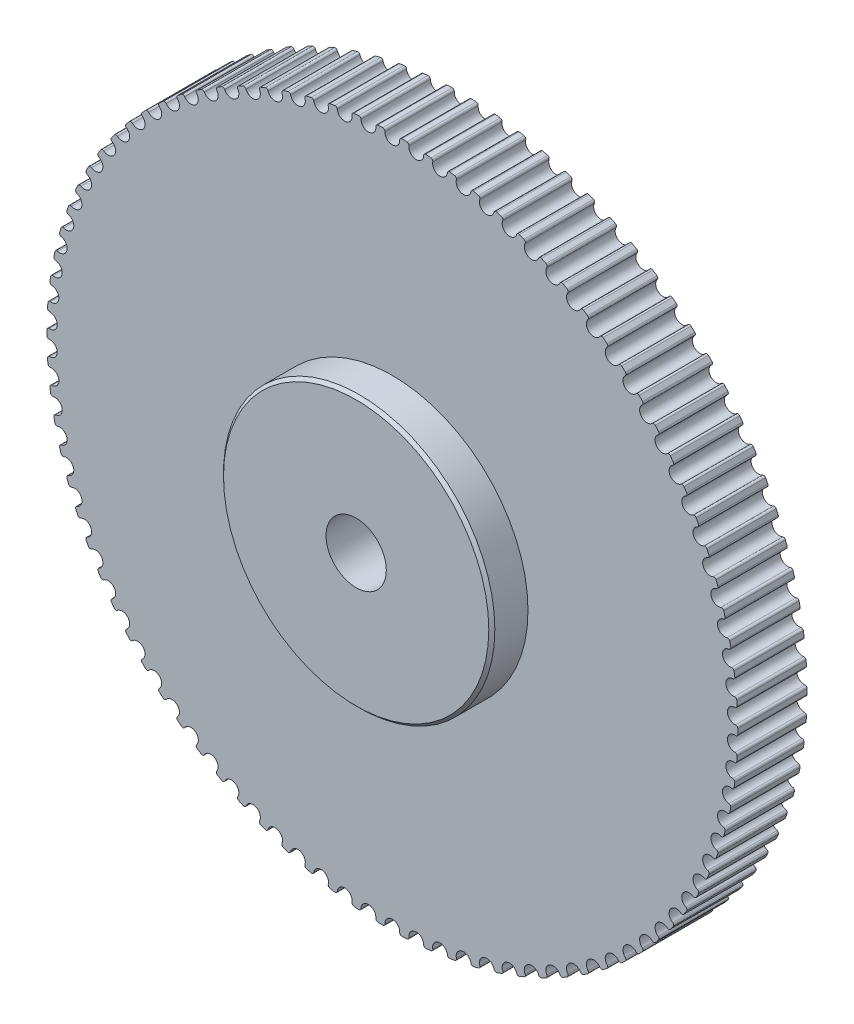
SolidWorks part; units mm, degrees
ref_plane "Ön Düzlem" through (0, 0, 0) normal (0, 0, 1) x (1, 0, 0)
ref_plane "Üst Düzlem" through (0, 0, 0) normal (0, 1, 0) x (1, 0, 0)
ref_plane "Sağ Düzlem" through (0, 0, 0) normal (1, 0, 0) x (0, 0, -1)
sketch "Çizim1" plane through (0, 0, 0) normal (0, 0, 1) x (1, 0, 0)
  arc A2 (0, 111.23) -> (2.457, 113.8116) centre (0, 113.69) ccw
  arc A3 (5.4881, 113.7058) -> (7.759, 110.959) centre (7.9306, 113.4131) ccw
  arc A4 (3.1755, 114.546) -> (2.457, 113.8116) centre (3.1561, 113.8463) ccw
  arc A5 (5.4881, 113.7058) -> (4.8225, 114.4885) centre (4.7931, 113.7891) ccw
  arc A6 (4.8225, 114.4885) -> (3.1755, 114.546) centre (0, 0) ccw
  arc A7 (7.759, 110.959) -> (10.3901, 113.363) centre (7.9306, 113.4131) ccw
  arc A8 (11.1581, 114.0454) -> (10.3901, 113.363) centre (11.09, 113.3488) ccw
  arc A9 (12.7971, 113.8732) -> (11.1581, 114.0454) centre (0, 0) ccw
  arc A10 (13.4064, 113.046) -> (12.7971, 113.8732) centre (12.7189, 113.1776) ccw
  arc A11 (13.4064, 113.046) -> (15.4802, 110.1475) centre (15.8226, 112.5836) ccw
  arc A12 (15.4802, 110.1475) -> (18.2726, 112.3621) centre (15.8226, 112.5836) ccw
  arc A13 (19.0863, 112.9893) -> (18.2726, 112.3621) centre (18.9698, 112.2991) ccw
  arc A14 (20.7093, 112.7031) -> (19.0863, 112.9893) centre (0, 0) ccw
  arc A15 (21.2595, 111.8354) -> (20.7093, 112.7031) centre (20.5828, 112.0146) ccw
  arc A16 (21.2595, 111.8354) -> (23.126, 108.7994) centre (23.6375, 111.2056) ccw
  arc A17 (23.126, 108.7994) -> (26.0661, 110.8138) centre (23.6375, 111.2056) ccw
  arc A18 (26.9216, 111.3827) -> (26.0661, 110.8138) centre (26.7571, 110.7022) ccw
  arc A19 (28.5206, 110.984) -> (26.9216, 111.3827) centre (0, 0) ccw
  arc A20 (29.0089, 110.08) -> (28.5206, 110.984) centre (28.3464, 110.306) ccw
  arc A21 (29.0089, 110.08) -> (30.6591, 106.9211) centre (31.3372, 109.2858) ccw
  arc A22 (30.6591, 106.9211) -> (33.7326, 108.7255) centre (31.3372, 109.2858) ccw
  arc A23 (34.6257, 109.2334) -> (33.7326, 108.7255) centre (34.4142, 108.5661) ccw
  arc A24 (36.193, 108.7241) -> (34.6257, 109.2334) centre (0, 0) ccw
  arc A25 (36.6171, 107.7883) -> (36.193, 108.7241) centre (35.9719, 108.06) ccw
  arc A26 (36.6171, 107.7883) -> (38.0429, 104.522) centre (38.8843, 106.8337) ccw
  arc A27 (38.0429, 104.522) -> (41.2347, 106.1076) centre (38.8843, 106.8337) ccw
  arc A28 (42.1611, 106.5519) -> (41.2347, 106.1076) centre (41.9035, 105.901) ccw
  arc A29 (43.6891, 105.9346) -> (42.1611, 106.5519) centre (0, 0) ccw
  arc A30 (44.0468, 104.9715) -> (43.6891, 105.9346) centre (43.4222, 105.2874) ccw
  arc A31 (44.0468, 104.9715) -> (45.2413, 101.6137) centre (46.2419, 103.861) ccw
  arc A32 (45.2413, 101.6137) -> (48.5359, 102.9728) centre (46.2419, 103.861) ccw
  arc A33 (49.491, 103.3514) -> (48.5359, 102.9728) centre (49.1887, 102.72) ccw
  arc A34 (50.9723, 102.6289) -> (49.491, 103.3514) centre (0, 0) ccw
  arc A35 (51.2619, 101.6432) -> (50.9723, 102.6289) centre (50.6609, 102.002) ccw
  arc A36 (51.2619, 101.6432) -> (52.2193, 98.2103) centre (53.3742, 100.3823) ccw
  arc A37 (52.2193, 98.2103) -> (55.6007, 99.3362) centre (53.3742, 100.3823) ccw
  arc A38 (56.5799, 99.6473) -> (55.6007, 99.3362) centre (56.2343, 99.0386) ccw
  arc A39 (58.0071, 98.8233) -> (56.5799, 99.6473) centre (0, 0) ccw
  arc A40 (58.2273, 97.8198) -> (58.0071, 98.8233) centre (57.6528, 98.2196) ccw
  arc A41 (58.2273, 97.8198) -> (58.9429, 94.3284) centre (60.2465, 96.4146) ccw
  arc A42 (58.9429, 94.3284) -> (62.3946, 95.2157) centre (60.2465, 96.4146) ccw
  arc A43 (63.3931, 95.4577) -> (62.3946, 95.2157) centre (63.0059, 94.8746) ccw
  arc A44 (64.7594, 94.5362) -> (63.3931, 95.4577) centre (0, 0) ccw
  arc A45 (64.9091, 93.5197) -> (64.7594, 94.5362) centre (64.3638, 93.9587) ccw
  arc A46 (64.9091, 93.5197) -> (65.3794, 89.987) centre (66.8253, 91.9771) ccw
  arc A47 (65.3794, 89.987) -> (68.8846, 90.6314) centre (66.8253, 91.9771) ccw
  arc A48 (69.8975, 90.8031) -> (68.8846, 90.6314) centre (69.4705, 90.2484) ccw
  arc A49 (71.1961, 89.7885) -> (69.8975, 90.8031) centre (0, 0) ccw
  arc A50 (71.2746, 88.7641) -> (71.1961, 89.7885) centre (70.7612, 89.24) ccw
  arc A51 (71.2746, 88.7641) -> (71.4973, 85.2071) centre (73.0785, 87.0916) ccw
  arc A52 (71.4973, 85.2071) -> (75.0389, 85.6055) centre (73.0785, 87.0916) ccw
  arc A53 (76.0613, 85.7061) -> (75.0389, 85.6055) centre (75.5967, 85.1826) ccw
  arc A54 (77.286, 84.6034) -> (76.0613, 85.7061) centre (0, 0) ccw
  arc A55 (77.2928, 83.576) -> (77.286, 84.6034) centre (76.8139, 84.0866) ccw
  arc A56 (77.2928, 83.576) -> (77.2669, 80.0122) centre (78.9757, 81.7817) ccw
  arc A57 (77.2669, 80.0122) -> (80.8276, 80.1625) centre (78.9757, 81.7817) ccw
  arc A58 (81.8546, 80.1916) -> (80.8276, 80.1625) centre (81.3546, 79.7017) ccw
  arc A59 (82.9994, 79.0061) -> (81.8546, 80.1916) centre (0, 0) ccw
  arc A60 (82.9345, 77.9808) -> (82.9994, 79.0061) centre (82.4924, 78.5235) ccw
  arc A61 (82.9345, 77.9808) -> (82.66, 74.4274) centre (84.4881, 76.0735) ccw
  arc A62 (82.66, 74.4274) -> (86.2226, 74.329) centre (84.4881, 76.0735) ccw
  arc A63 (87.2491, 74.2863) -> (86.2226, 74.329) centre (86.7161, 73.8326) ccw
  arc A64 (88.3084, 73.0239) -> (87.2491, 74.2863) centre (0, 0) ccw
  arc A65 (88.1721, 72.0056) -> (88.3084, 73.0239) centre (87.769, 72.5778) ccw
  arc A66 (88.1721, 72.0056) -> (87.6504, 68.48) centre (89.5889, 69.9946) ccw
  arc A67 (87.6504, 68.48) -> (91.1975, 68.1333) centre (89.5889, 69.9946) ccw
  arc A68 (92.2185, 68.0192) -> (91.1975, 68.1333) centre (91.6552, 67.6037) ccw
  arc A69 (93.1872, 66.6859) -> (92.2185, 68.0192) centre (0, 0) ccw
  arc A70 (92.9802, 65.6796) -> (93.1872, 66.6859) centre (92.6179, 66.2786) ccw
  arc A71 (92.9802, 65.6796) -> (92.2138, 62.199) centre (94.2533, 63.5746) ccw
  arc A72 (92.2138, 62.199) -> (95.7281, 61.6057) centre (94.2533, 63.5746) ccw
  arc A73 (96.7387, 61.4207) -> (95.7281, 61.6057) centre (96.1477, 61.0455) ccw
  arc A74 (97.612, 60.0231) -> (96.7387, 61.4207) centre (0, 0) ccw
  arc A75 (97.3353, 59.0336) -> (97.612, 60.0231) centre (97.0157, 59.6564) ccw
  arc A76 (97.3353, 59.0336) -> (96.328, 55.615) centre (98.4584, 56.845) ccw
  arc A77 (96.328, 55.615) -> (99.7923, 54.778) centre (98.4584, 56.845) ccw
  arc A78 (100.7875, 54.5229) -> (99.7923, 54.778) centre (100.1718, 54.1898) ccw
  arc A79 (101.5612, 53.0678) -> (100.7875, 54.5229) centre (0, 0) ccw
  arc A80 (101.2162, 52.1001) -> (101.5612, 53.0678) centre (100.9408, 52.7436) ccw
  arc A81 (101.2162, 52.1001) -> (99.9729, 48.76) centre (102.1839, 49.8384) ccw
  arc A82 (99.9729, 48.76) -> (103.3703, 47.6834) centre (102.1839, 49.8384) ccw
  arc A83 (104.3453, 47.3595) -> (103.3703, 47.6834) centre (103.7079, 47.0702) ccw
  arc A84 (105.0156, 45.854) -> (104.3453, 47.3595) centre (0, 0) ccw
  arc A85 (104.6039, 44.9127) -> (105.0156, 45.854) centre (104.3741, 45.5739) ccw
  arc A86 (104.6039, 44.9127) -> (103.1307, 41.6675) centre (105.4115, 42.589) ccw
  arc A87 (103.1307, 41.6675) -> (106.4447, 40.3565) centre (105.4115, 42.589) ccw
  arc A88 (107.3948, 39.9654) -> (106.4447, 40.3565) centre (106.7387, 39.7212) ccw
  arc A89 (107.9584, 38.4168) -> (107.3948, 39.9654) centre (0, 0) ccw
  arc A90 (107.4821, 37.5065) -> (107.9584, 38.4168) centre (107.2989, 38.1821) ccw
  arc A91 (107.4821, 37.5065) -> (105.786, 34.372) centre (108.1256, 35.1321) ccw
  arc A92 (105.786, 34.372) -> (109.0006, 32.833) centre (108.1256, 35.1321) ccw
  arc A93 (109.921, 32.3765) -> (109.0006, 32.833) centre (109.2495, 32.1788) ccw
  arc A94 (110.3753, 30.7924) -> (109.921, 32.3765) centre (0, 0) ccw
  arc A95 (109.8366, 29.9175) -> (110.3753, 30.7924) centre (109.701, 30.6043) ccw
  arc A96 (109.8366, 29.9175) -> (107.926, 26.909) centre (110.3129, 27.5041) ccw
  arc A97 (107.926, 26.909) -> (111.0254, 25.1495) centre (110.3129, 27.5041) ccw
  arc A98 (111.9117, 24.63) -> (111.0254, 25.1495) centre (111.2281, 24.4795) ccw
  arc A99 (112.2544, 23.018) -> (111.9117, 24.63) centre (0, 0) ccw
  arc A100 (111.6559, 22.1828) -> (112.2544, 23.018) centre (111.5686, 22.8774) ccw
  arc A101 (111.6559, 22.1828) -> (109.5402, 19.3149) centre (111.9628, 19.7421) ccw
  arc A102 (109.5402, 19.3149) -> (112.5092, 17.3435) centre (111.9628, 19.7421) ccw
  arc A103 (113.3572, 16.7634) -> (112.5092, 17.3435) centre (112.6647, 16.661) ccw
  arc A104 (113.5866, 15.1315) -> (113.3572, 16.7634) centre (0, 0) ccw
  arc A105 (112.9313, 14.3401) -> (113.5866, 15.1315) centre (112.8927, 15.039) ccw
  arc A106 (112.9313, 14.3401) -> (110.6207, 11.6267) centre (113.0672, 11.8838) ccw
  arc A107 (110.6207, 11.6267) -> (113.445, 9.453) centre (113.0672, 11.8838) ccw
  arc A108 (114.2504, 8.8152) -> (113.445, 9.453) centre (113.5525, 8.7613) ccw
  arc A109 (114.3654, 7.1712) -> (114.2504, 8.8152) centre (0, 0) ccw
  arc A110 (113.6566, 6.4275) -> (114.3654, 7.1712) centre (113.6668, 7.1274) ccw
  arc A111 (113.6566, 6.4275) -> (111.1622, 3.8819) centre (113.6207, 3.9677) ccw
  arc A112 (111.1622, 3.8819) -> (113.8281, 1.5165) centre (113.6207, 3.9677) ccw
  arc A113 (114.587, 0.824) -> (113.8281, 1.5165) centre (113.8871, 0.819) ccw
  arc A114 (114.587, -0.824) -> (114.587, 0.824) centre (0, 0) ccw
  arc A115 (113.8281, -1.5165) -> (114.587, -0.824) centre (113.8871, -0.819) ccw
  arc A116 (113.8281, -1.5165) -> (111.1622, -3.8819) centre (113.6207, -3.9677) ccw
  arc A117 (111.1622, -3.8819) -> (113.6566, -6.4275) centre (113.6207, -3.9677) ccw
  arc A118 (114.3654, -7.1712) -> (113.6566, -6.4275) centre (113.6668, -7.1274) ccw
  arc A119 (114.2504, -8.8152) -> (114.3654, -7.1712) centre (0, 0) ccw
  arc A120 (113.445, -9.453) -> (114.2504, -8.8152) centre (113.5525, -8.7613) ccw
  arc A121 (113.445, -9.453) -> (110.6207, -11.6267) centre (113.0672, -11.8838) ccw
  arc A122 (110.6207, -11.6267) -> (112.9313, -14.3401) centre (113.0672, -11.8838) ccw
  arc A123 (113.5866, -15.1315) -> (112.9313, -14.3401) centre (112.8927, -15.039) ccw
  arc A124 (113.3572, -16.7634) -> (113.5866, -15.1315) centre (0, 0) ccw
  arc A125 (112.5092, -17.3435) -> (113.3572, -16.7634) centre (112.6647, -16.661) ccw
  arc A126 (112.5092, -17.3435) -> (109.5402, -19.3149) centre (111.9628, -19.7421) ccw
  arc A127 (109.5402, -19.3149) -> (111.6559, -22.1828) centre (111.9628, -19.7421) ccw
  arc A128 (112.2544, -23.018) -> (111.6559, -22.1828) centre (111.5686, -22.8774) ccw
  arc A129 (111.9117, -24.63) -> (112.2544, -23.018) centre (0, 0) ccw
  arc A130 (111.0254, -25.1495) -> (111.9117, -24.63) centre (111.2281, -24.4795) ccw
  arc A131 (111.0254, -25.1495) -> (107.926, -26.909) centre (110.3129, -27.5041) ccw
  arc A132 (107.926, -26.909) -> (109.8366, -29.9175) centre (110.3129, -27.5041) ccw
  arc A133 (110.3753, -30.7924) -> (109.8366, -29.9175) centre (109.701, -30.6043) ccw
  arc A134 (109.921, -32.3765) -> (110.3753, -30.7924) centre (0, 0) ccw
  arc A135 (109.0006, -32.833) -> (109.921, -32.3765) centre (109.2495, -32.1788) ccw
  arc A136 (109.0006, -32.833) -> (105.786, -34.372) centre (108.1256, -35.1321) ccw
  arc A137 (105.786, -34.372) -> (107.4821, -37.5065) centre (108.1256, -35.1321) ccw
  arc A138 (107.9584, -38.4168) -> (107.4821, -37.5065) centre (107.2989, -38.1821) ccw
  arc A139 (107.3948, -39.9654) -> (107.9584, -38.4168) centre (0, 0) ccw
  arc A140 (106.4447, -40.3565) -> (107.3948, -39.9654) centre (106.7387, -39.7212) ccw
  arc A141 (106.4447, -40.3565) -> (103.1307, -41.6675) centre (105.4115, -42.589) ccw
  arc A142 (103.1307, -41.6675) -> (104.6039, -44.9127) centre (105.4115, -42.589) ccw
  arc A143 (105.0156, -45.854) -> (104.6039, -44.9127) centre (104.3741, -45.5739) ccw
  arc A144 (104.3453, -47.3595) -> (105.0156, -45.854) centre (0, 0) ccw
  arc A145 (103.3703, -47.6834) -> (104.3453, -47.3595) centre (103.7079, -47.0702) ccw
  arc A146 (103.3703, -47.6834) -> (99.9729, -48.76) centre (102.1839, -49.8384) ccw
  arc A147 (99.9729, -48.76) -> (101.2162, -52.1001) centre (102.1839, -49.8384) ccw
  arc A148 (101.5612, -53.0678) -> (101.2162, -52.1001) centre (100.9408, -52.7436) ccw
  arc A149 (100.7875, -54.5229) -> (101.5612, -53.0678) centre (0, 0) ccw
  arc A150 (99.7923, -54.778) -> (100.7875, -54.5229) centre (100.1718, -54.1898) ccw
  arc A151 (99.7923, -54.778) -> (96.328, -55.615) centre (98.4584, -56.845) ccw
  arc A152 (96.328, -55.615) -> (97.3353, -59.0336) centre (98.4584, -56.845) ccw
  arc A153 (97.612, -60.0231) -> (97.3353, -59.0336) centre (97.0157, -59.6564) ccw
  arc A154 (96.7387, -61.4207) -> (97.612, -60.0231) centre (0, 0) ccw
  arc A155 (95.7281, -61.6057) -> (96.7387, -61.4207) centre (96.1477, -61.0455) ccw
  arc A156 (95.7281, -61.6057) -> (92.2138, -62.199) centre (94.2533, -63.5746) ccw
  arc A157 (92.2138, -62.199) -> (92.9802, -65.6796) centre (94.2533, -63.5746) ccw
  arc A158 (93.1872, -66.6859) -> (92.9802, -65.6796) centre (92.6179, -66.2786) ccw
  arc A159 (92.2185, -68.0192) -> (93.1872, -66.6859) centre (0, 0) ccw
  arc A160 (91.1975, -68.1333) -> (92.2185, -68.0192) centre (91.6552, -67.6037) ccw
  arc A161 (91.1975, -68.1333) -> (87.6504, -68.48) centre (89.5889, -69.9946) ccw
  arc A162 (87.6504, -68.48) -> (88.1721, -72.0056) centre (89.5889, -69.9946) ccw
  arc A163 (88.3084, -73.0239) -> (88.1721, -72.0056) centre (87.769, -72.5778) ccw
  arc A164 (87.2491, -74.2863) -> (88.3084, -73.0239) centre (0, 0) ccw
  arc A165 (86.2226, -74.329) -> (87.2491, -74.2863) centre (86.7161, -73.8326) ccw
  arc A166 (86.2226, -74.329) -> (82.66, -74.4274) centre (84.4881, -76.0735) ccw
  arc A167 (82.66, -74.4274) -> (82.9345, -77.9808) centre (84.4881, -76.0735) ccw
  arc A168 (82.9994, -79.0061) -> (82.9345, -77.9808) centre (82.4924, -78.5235) ccw
  arc A169 (81.8546, -80.1916) -> (82.9994, -79.0061) centre (0, 0) ccw
  arc A170 (80.8276, -80.1625) -> (81.8546, -80.1916) centre (81.3546, -79.7017) ccw
  arc A171 (80.8276, -80.1625) -> (77.2669, -80.0122) centre (78.9757, -81.7817) ccw
  arc A172 (77.2669, -80.0122) -> (77.2928, -83.576) centre (78.9757, -81.7817) ccw
  arc A173 (77.286, -84.6034) -> (77.2928, -83.576) centre (76.8139, -84.0866) ccw
  arc A174 (76.0613, -85.7061) -> (77.286, -84.6034) centre (0, 0) ccw
  arc A175 (75.0389, -85.6055) -> (76.0613, -85.7061) centre (75.5967, -85.1826) ccw
  arc A176 (75.0389, -85.6055) -> (71.4973, -85.2071) centre (73.0785, -87.0916) ccw
  arc A177 (71.4973, -85.2071) -> (71.2746, -88.7641) centre (73.0785, -87.0916) ccw
  arc A178 (71.1961, -89.7885) -> (71.2746, -88.7641) centre (70.7612, -89.24) ccw
  arc A179 (69.8975, -90.8031) -> (71.1961, -89.7885) centre (0, 0) ccw
  arc A180 (68.8846, -90.6314) -> (69.8975, -90.8031) centre (69.4705, -90.2484) ccw
  arc A181 (68.8846, -90.6314) -> (65.3794, -89.987) centre (66.8253, -91.9771) ccw
  arc A182 (65.3794, -89.987) -> (64.9091, -93.5197) centre (66.8253, -91.9771) ccw
  arc A183 (64.7594, -94.5362) -> (64.9091, -93.5197) centre (64.3638, -93.9587) ccw
  arc A184 (63.3931, -95.4577) -> (64.7594, -94.5362) centre (0, 0) ccw
  arc A185 (62.3946, -95.2157) -> (63.3931, -95.4577) centre (63.0059, -94.8746) ccw
  arc A186 (62.3946, -95.2157) -> (58.9429, -94.3284) centre (60.2465, -96.4146) ccw
  arc A187 (58.9429, -94.3284) -> (58.2273, -97.8198) centre (60.2465, -96.4146) ccw
  arc A188 (58.0071, -98.8233) -> (58.2273, -97.8198) centre (57.6528, -98.2196) ccw
  arc A189 (56.5799, -99.6473) -> (58.0071, -98.8233) centre (0, 0) ccw
  arc A190 (55.6007, -99.3362) -> (56.5799, -99.6473) centre (56.2343, -99.0386) ccw
  arc A191 (55.6007, -99.3362) -> (52.2193, -98.2103) centre (53.3742, -100.3823) ccw
  arc A192 (52.2193, -98.2103) -> (51.2619, -101.6432) centre (53.3742, -100.3823) ccw
  arc A193 (50.9723, -102.6289) -> (51.2619, -101.6432) centre (50.6609, -102.002) ccw
  arc A194 (49.491, -103.3514) -> (50.9723, -102.6289) centre (0, 0) ccw
  arc A195 (48.5359, -102.9728) -> (49.491, -103.3514) centre (49.1887, -102.72) ccw
  arc A196 (48.5359, -102.9728) -> (45.2413, -101.6137) centre (46.2419, -103.861) ccw
  arc A197 (45.2413, -101.6137) -> (44.0468, -104.9715) centre (46.2419, -103.861) ccw
  arc A198 (43.6891, -105.9346) -> (44.0468, -104.9715) centre (43.4222, -105.2874) ccw
  arc A199 (42.1611, -106.5519) -> (43.6891, -105.9346) centre (0, 0) ccw
  arc A200 (41.2347, -106.1076) -> (42.1611, -106.5519) centre (41.9035, -105.901) ccw
  arc A201 (41.2347, -106.1076) -> (38.0429, -104.522) centre (38.8843, -106.8337) ccw
  arc A202 (38.0429, -104.522) -> (36.6171, -107.7883) centre (38.8843, -106.8337) ccw
  arc A203 (36.193, -108.7241) -> (36.6171, -107.7883) centre (35.9719, -108.06) ccw
  arc A204 (34.6257, -109.2334) -> (36.193, -108.7241) centre (0, 0) ccw
  arc A205 (33.7326, -108.7255) -> (34.6257, -109.2334) centre (34.4142, -108.5661) ccw
  arc A206 (33.7326, -108.7255) -> (30.6591, -106.9211) centre (31.3372, -109.2858) ccw
  arc A207 (30.6591, -106.9211) -> (29.0089, -110.08) centre (31.3372, -109.2858) ccw
  arc A208 (28.5206, -110.984) -> (29.0089, -110.08) centre (28.3464, -110.306) ccw
  arc A209 (26.9216, -111.3827) -> (28.5206, -110.984) centre (0, 0) ccw
  arc A210 (26.0661, -110.8138) -> (26.9216, -111.3827) centre (26.7571, -110.7022) ccw
  arc A211 (26.0661, -110.8138) -> (23.126, -108.7994) centre (23.6375, -111.2056) ccw
  arc A212 (23.126, -108.7994) -> (21.2595, -111.8354) centre (23.6375, -111.2056) ccw
  arc A213 (20.7093, -112.7031) -> (21.2595, -111.8354) centre (20.5828, -112.0146) ccw
  arc A214 (19.0863, -112.9893) -> (20.7093, -112.7031) centre (0, 0) ccw
  arc A215 (18.2726, -112.3621) -> (19.0863, -112.9893) centre (18.9698, -112.2991) ccw
  arc A216 (18.2726, -112.3621) -> (15.4802, -110.1475) centre (15.8226, -112.5836) ccw
  arc A217 (15.4802, -110.1475) -> (13.4064, -113.046) centre (15.8226, -112.5836) ccw
  arc A218 (12.7971, -113.8732) -> (13.4064, -113.046) centre (12.7189, -113.1776) ccw
  arc A219 (11.1581, -114.0454) -> (12.7971, -113.8732) centre (0, 0) ccw
  arc A220 (10.3901, -113.363) -> (11.1581, -114.0454) centre (11.09, -113.3488) ccw
  arc A221 (10.3901, -113.363) -> (7.759, -110.959) centre (7.9306, -113.4131) ccw
  arc A222 (7.759, -110.959) -> (5.4881, -113.7058) centre (7.9306, -113.4131) ccw
  arc A223 (4.8225, -114.4885) -> (5.4881, -113.7058) centre (4.7931, -113.7891) ccw
  arc A224 (3.1755, -114.546) -> (4.8225, -114.4885) centre (0, 0) ccw
  arc A225 (2.457, -113.8116) -> (3.1755, -114.546) centre (3.1561, -113.8463) ccw
  arc A226 (2.457, -113.8116) -> (0, -111.23) centre (0, -113.69) ccw
  arc A227 (0, -111.23) -> (-2.457, -113.8116) centre (0, -113.69) ccw
  arc A228 (-3.1755, -114.546) -> (-2.457, -113.8116) centre (-3.1561, -113.8463) ccw
  arc A229 (-4.8225, -114.4885) -> (-3.1755, -114.546) centre (0, 0) ccw
  arc A230 (-5.4881, -113.7058) -> (-4.8225, -114.4885) centre (-4.7931, -113.7891) ccw
  arc A231 (-5.4881, -113.7058) -> (-7.759, -110.959) centre (-7.9306, -113.4131) ccw
  arc A232 (-7.759, -110.959) -> (-10.3901, -113.363) centre (-7.9306, -113.4131) ccw
  arc A233 (-11.1581, -114.0454) -> (-10.3901, -113.363) centre (-11.09, -113.3488) ccw
  arc A234 (-12.7971, -113.8732) -> (-11.1581, -114.0454) centre (0, 0) ccw
  arc A235 (-13.4064, -113.046) -> (-12.7971, -113.8732) centre (-12.7189, -113.1776) ccw
  arc A236 (-13.4064, -113.046) -> (-15.4802, -110.1475) centre (-15.8226, -112.5836) ccw
  arc A237 (-15.4802, -110.1475) -> (-18.2726, -112.3621) centre (-15.8226, -112.5836) ccw
  arc A238 (-19.0863, -112.9893) -> (-18.2726, -112.3621) centre (-18.9698, -112.2991) ccw
  arc A239 (-20.7093, -112.7031) -> (-19.0863, -112.9893) centre (0, 0) ccw
  arc A240 (-21.2595, -111.8354) -> (-20.7093, -112.7031) centre (-20.5828, -112.0146) ccw
  arc A241 (-21.2595, -111.8354) -> (-23.126, -108.7994) centre (-23.6375, -111.2056) ccw
  arc A242 (-23.126, -108.7994) -> (-26.0661, -110.8138) centre (-23.6375, -111.2056) ccw
  arc A243 (-26.9216, -111.3827) -> (-26.0661, -110.8138) centre (-26.7571, -110.7022) ccw
  arc A244 (-28.5206, -110.984) -> (-26.9216, -111.3827) centre (0, 0) ccw
  arc A245 (-29.0089, -110.08) -> (-28.5206, -110.984) centre (-28.3464, -110.306) ccw
  arc A246 (-29.0089, -110.08) -> (-30.6591, -106.9211) centre (-31.3372, -109.2858) ccw
  arc A247 (-30.6591, -106.9211) -> (-33.7326, -108.7255) centre (-31.3372, -109.2858) ccw
  arc A248 (-34.6257, -109.2334) -> (-33.7326, -108.7255) centre (-34.4142, -108.5661) ccw
  arc A249 (-36.193, -108.7241) -> (-34.6257, -109.2334) centre (0, 0) ccw
  arc A250 (-36.6171, -107.7883) -> (-36.193, -108.7241) centre (-35.9719, -108.06) ccw
  arc A251 (-36.6171, -107.7883) -> (-38.0429, -104.522) centre (-38.8843, -106.8337) ccw
  arc A252 (-38.0429, -104.522) -> (-41.2347, -106.1076) centre (-38.8843, -106.8337) ccw
  arc A253 (-42.1611, -106.5519) -> (-41.2347, -106.1076) centre (-41.9035, -105.901) ccw
  arc A254 (-43.6891, -105.9346) -> (-42.1611, -106.5519) centre (0, 0) ccw
  arc A255 (-44.0468, -104.9715) -> (-43.6891, -105.9346) centre (-43.4222, -105.2874) ccw
  arc A256 (-44.0468, -104.9715) -> (-45.2413, -101.6137) centre (-46.2419, -103.861) ccw
  arc A257 (-45.2413, -101.6137) -> (-48.5359, -102.9728) centre (-46.2419, -103.861) ccw
  arc A258 (-49.491, -103.3514) -> (-48.5359, -102.9728) centre (-49.1887, -102.72) ccw
  arc A259 (-50.9723, -102.6289) -> (-49.491, -103.3514) centre (0, 0) ccw
  arc A260 (-51.2619, -101.6432) -> (-50.9723, -102.6289) centre (-50.6609, -102.002) ccw
  arc A261 (-51.2619, -101.6432) -> (-52.2193, -98.2103) centre (-53.3742, -100.3823) ccw
  arc A262 (-52.2193, -98.2103) -> (-55.6007, -99.3362) centre (-53.3742, -100.3823) ccw
  arc A263 (-56.5799, -99.6473) -> (-55.6007, -99.3362) centre (-56.2343, -99.0386) ccw
  arc A264 (-58.0071, -98.8233) -> (-56.5799, -99.6473) centre (0, 0) ccw
  arc A265 (-58.2273, -97.8198) -> (-58.0071, -98.8233) centre (-57.6528, -98.2196) ccw
  arc A266 (-58.2273, -97.8198) -> (-58.9429, -94.3284) centre (-60.2465, -96.4146) ccw
  arc A267 (-58.9429, -94.3284) -> (-62.3946, -95.2157) centre (-60.2465, -96.4146) ccw
  arc A268 (-63.3931, -95.4577) -> (-62.3946, -95.2157) centre (-63.0059, -94.8746) ccw
  arc A269 (-64.7594, -94.5362) -> (-63.3931, -95.4577) centre (0, 0) ccw
  arc A270 (-64.9091, -93.5197) -> (-64.7594, -94.5362) centre (-64.3638, -93.9587) ccw
  arc A271 (-64.9091, -93.5197) -> (-65.3794, -89.987) centre (-66.8253, -91.9771) ccw
  arc A272 (-65.3794, -89.987) -> (-68.8846, -90.6314) centre (-66.8253, -91.9771) ccw
  arc A273 (-69.8975, -90.8031) -> (-68.8846, -90.6314) centre (-69.4705, -90.2484) ccw
  arc A274 (-71.1961, -89.7885) -> (-69.8975, -90.8031) centre (0, 0) ccw
  arc A275 (-71.2746, -88.7641) -> (-71.1961, -89.7885) centre (-70.7612, -89.24) ccw
  arc A276 (-71.2746, -88.7641) -> (-71.4973, -85.2071) centre (-73.0785, -87.0916) ccw
  arc A277 (-71.4973, -85.2071) -> (-75.0389, -85.6055) centre (-73.0785, -87.0916) ccw
  arc A278 (-76.0613, -85.7061) -> (-75.0389, -85.6055) centre (-75.5967, -85.1826) ccw
  arc A279 (-77.286, -84.6034) -> (-76.0613, -85.7061) centre (0, 0) ccw
  arc A280 (-77.2928, -83.576) -> (-77.286, -84.6034) centre (-76.8139, -84.0866) ccw
  arc A281 (-77.2928, -83.576) -> (-77.2669, -80.0122) centre (-78.9757, -81.7817) ccw
  arc A282 (-77.2669, -80.0122) -> (-80.8276, -80.1625) centre (-78.9757, -81.7817) ccw
  arc A283 (-81.8546, -80.1916) -> (-80.8276, -80.1625) centre (-81.3546, -79.7017) ccw
  arc A284 (-82.9994, -79.0061) -> (-81.8546, -80.1916) centre (0, 0) ccw
  arc A285 (-82.9345, -77.9808) -> (-82.9994, -79.0061) centre (-82.4924, -78.5235) ccw
  arc A286 (-82.9345, -77.9808) -> (-82.66, -74.4274) centre (-84.4881, -76.0735) ccw
  arc A287 (-82.66, -74.4274) -> (-86.2226, -74.329) centre (-84.4881, -76.0735) ccw
  arc A288 (-87.2491, -74.2863) -> (-86.2226, -74.329) centre (-86.7161, -73.8326) ccw
  arc A289 (-88.3084, -73.0239) -> (-87.2491, -74.2863) centre (0, 0) ccw
  arc A290 (-88.1721, -72.0056) -> (-88.3084, -73.0239) centre (-87.769, -72.5778) ccw
  arc A291 (-88.1721, -72.0056) -> (-87.6504, -68.48) centre (-89.5889, -69.9946) ccw
  arc A292 (-87.6504, -68.48) -> (-91.1975, -68.1333) centre (-89.5889, -69.9946) ccw
  arc A293 (-92.2185, -68.0192) -> (-91.1975, -68.1333) centre (-91.6552, -67.6037) ccw
  arc A294 (-93.1872, -66.6859) -> (-92.2185, -68.0192) centre (0, 0) ccw
  arc A295 (-92.9802, -65.6796) -> (-93.1872, -66.6859) centre (-92.6179, -66.2786) ccw
  arc A296 (-92.9802, -65.6796) -> (-92.2138, -62.199) centre (-94.2533, -63.5746) ccw
  arc A297 (-92.2138, -62.199) -> (-95.7281, -61.6057) centre (-94.2533, -63.5746) ccw
  arc A298 (-96.7387, -61.4207) -> (-95.7281, -61.6057) centre (-96.1477, -61.0455) ccw
  arc A299 (-97.612, -60.0231) -> (-96.7387, -61.4207) centre (0, 0) ccw
  arc A300 (-97.3353, -59.0336) -> (-97.612, -60.0231) centre (-97.0157, -59.6564) ccw
  arc A301 (-97.3353, -59.0336) -> (-96.328, -55.615) centre (-98.4584, -56.845) ccw
  arc A302 (-96.328, -55.615) -> (-99.7923, -54.778) centre (-98.4584, -56.845) ccw
  arc A303 (-100.7875, -54.5229) -> (-99.7923, -54.778) centre (-100.1718, -54.1898) ccw
  arc A304 (-101.5612, -53.0678) -> (-100.7875, -54.5229) centre (0, 0) ccw
  arc A305 (-101.2162, -52.1001) -> (-101.5612, -53.0678) centre (-100.9408, -52.7436) ccw
  arc A306 (-101.2162, -52.1001) -> (-99.9729, -48.76) centre (-102.1839, -49.8384) ccw
  arc A307 (-99.9729, -48.76) -> (-103.3703, -47.6834) centre (-102.1839, -49.8384) ccw
  arc A308 (-104.3453, -47.3595) -> (-103.3703, -47.6834) centre (-103.7079, -47.0702) ccw
  arc A309 (-105.0156, -45.854) -> (-104.3453, -47.3595) centre (0, 0) ccw
  arc A310 (-104.6039, -44.9127) -> (-105.0156, -45.854) centre (-104.3741, -45.5739) ccw
  arc A311 (-104.6039, -44.9127) -> (-103.1307, -41.6675) centre (-105.4115, -42.589) ccw
  arc A312 (-103.1307, -41.6675) -> (-106.4447, -40.3565) centre (-105.4115, -42.589) ccw
  arc A313 (-107.3948, -39.9654) -> (-106.4447, -40.3565) centre (-106.7387, -39.7212) ccw
  arc A314 (-107.9584, -38.4168) -> (-107.3948, -39.9654) centre (0, 0) ccw
  arc A315 (-107.4821, -37.5065) -> (-107.9584, -38.4168) centre (-107.2989, -38.1821) ccw
  arc A316 (-107.4821, -37.5065) -> (-105.786, -34.372) centre (-108.1256, -35.1321) ccw
  arc A317 (-105.786, -34.372) -> (-109.0006, -32.833) centre (-108.1256, -35.1321) ccw
  arc A318 (-109.921, -32.3765) -> (-109.0006, -32.833) centre (-109.2495, -32.1788) ccw
  arc A319 (-110.3753, -30.7924) -> (-109.921, -32.3765) centre (0, 0) ccw
  arc A320 (-109.8366, -29.9175) -> (-110.3753, -30.7924) centre (-109.701, -30.6043) ccw
  arc A321 (-109.8366, -29.9175) -> (-107.926, -26.909) centre (-110.3129, -27.5041) ccw
  arc A322 (-107.926, -26.909) -> (-111.0254, -25.1495) centre (-110.3129, -27.5041) ccw
  arc A323 (-111.9117, -24.63) -> (-111.0254, -25.1495) centre (-111.2281, -24.4795) ccw
  arc A324 (-112.2544, -23.018) -> (-111.9117, -24.63) centre (0, 0) ccw
  arc A325 (-111.6559, -22.1828) -> (-112.2544, -23.018) centre (-111.5686, -22.8774) ccw
  arc A326 (-111.6559, -22.1828) -> (-109.5402, -19.3149) centre (-111.9628, -19.7421) ccw
  arc A327 (-109.5402, -19.3149) -> (-112.5092, -17.3435) centre (-111.9628, -19.7421) ccw
  arc A328 (-113.3572, -16.7634) -> (-112.5092, -17.3435) centre (-112.6647, -16.661) ccw
  arc A329 (-113.5866, -15.1315) -> (-113.3572, -16.7634) centre (0, 0) ccw
  arc A330 (-112.9313, -14.3401) -> (-113.5866, -15.1315) centre (-112.8927, -15.039) ccw
  arc A331 (-112.9313, -14.3401) -> (-110.6207, -11.6267) centre (-113.0672, -11.8838) ccw
  arc A332 (-110.6207, -11.6267) -> (-113.445, -9.453) centre (-113.0672, -11.8838) ccw
  arc A333 (-114.2504, -8.8152) -> (-113.445, -9.453) centre (-113.5525, -8.7613) ccw
  arc A334 (-114.3654, -7.1712) -> (-114.2504, -8.8152) centre (0, 0) ccw
  arc A335 (-113.6566, -6.4275) -> (-114.3654, -7.1712) centre (-113.6668, -7.1274) ccw
  arc A336 (-113.6566, -6.4275) -> (-111.1622, -3.8819) centre (-113.6207, -3.9677) ccw
  arc A337 (-111.1622, -3.8819) -> (-113.8281, -1.5165) centre (-113.6207, -3.9677) ccw
  arc A338 (-114.587, -0.824) -> (-113.8281, -1.5165) centre (-113.8871, -0.819) ccw
  arc A339 (-114.587, 0.824) -> (-114.587, -0.824) centre (0, 0) ccw
  arc A340 (-113.8281, 1.5165) -> (-114.587, 0.824) centre (-113.8871, 0.819) ccw
  arc A341 (-113.8281, 1.5165) -> (-111.1622, 3.8819) centre (-113.6207, 3.9677) ccw
  arc A342 (-111.1622, 3.8819) -> (-113.6566, 6.4275) centre (-113.6207, 3.9677) ccw
  arc A343 (-114.3654, 7.1712) -> (-113.6566, 6.4275) centre (-113.6668, 7.1274) ccw
  arc A344 (-114.2504, 8.8152) -> (-114.3654, 7.1712) centre (0, 0) ccw
  arc A345 (-113.445, 9.453) -> (-114.2504, 8.8152) centre (-113.5525, 8.7613) ccw
  arc A346 (-113.445, 9.453) -> (-110.6207, 11.6267) centre (-113.0672, 11.8838) ccw
  arc A347 (-110.6207, 11.6267) -> (-112.9313, 14.3401) centre (-113.0672, 11.8838) ccw
  arc A348 (-113.5866, 15.1315) -> (-112.9313, 14.3401) centre (-112.8927, 15.039) ccw
  arc A349 (-113.3572, 16.7634) -> (-113.5866, 15.1315) centre (0, 0) ccw
  arc A350 (-112.5092, 17.3435) -> (-113.3572, 16.7634) centre (-112.6647, 16.661) ccw
  arc A351 (-112.5092, 17.3435) -> (-109.5402, 19.3149) centre (-111.9628, 19.7421) ccw
  arc A352 (-109.5402, 19.3149) -> (-111.6559, 22.1828) centre (-111.9628, 19.7421) ccw
  arc A353 (-112.2544, 23.018) -> (-111.6559, 22.1828) centre (-111.5686, 22.8774) ccw
  arc A354 (-111.9117, 24.63) -> (-112.2544, 23.018) centre (0, 0) ccw
  arc A355 (-111.0254, 25.1495) -> (-111.9117, 24.63) centre (-111.2281, 24.4795) ccw
  arc A356 (-111.0254, 25.1495) -> (-107.926, 26.909) centre (-110.3129, 27.5041) ccw
  arc A357 (-107.926, 26.909) -> (-109.8366, 29.9175) centre (-110.3129, 27.5041) ccw
  arc A358 (-110.3753, 30.7924) -> (-109.8366, 29.9175) centre (-109.701, 30.6043) ccw
  arc A359 (-109.921, 32.3765) -> (-110.3753, 30.7924) centre (0, 0) ccw
  arc A360 (-109.0006, 32.833) -> (-109.921, 32.3765) centre (-109.2495, 32.1788) ccw
  arc A361 (-109.0006, 32.833) -> (-105.786, 34.372) centre (-108.1256, 35.1321) ccw
  arc A362 (-105.786, 34.372) -> (-107.4821, 37.5065) centre (-108.1256, 35.1321) ccw
  arc A363 (-107.9584, 38.4168) -> (-107.4821, 37.5065) centre (-107.2989, 38.1821) ccw
  arc A364 (-107.3948, 39.9654) -> (-107.9584, 38.4168) centre (0, 0) ccw
  arc A365 (-106.4447, 40.3565) -> (-107.3948, 39.9654) centre (-106.7387, 39.7212) ccw
  arc A366 (-106.4447, 40.3565) -> (-103.1307, 41.6675) centre (-105.4115, 42.589) ccw
  arc A367 (-103.1307, 41.6675) -> (-104.6039, 44.9127) centre (-105.4115, 42.589) ccw
  arc A368 (-105.0156, 45.854) -> (-104.6039, 44.9127) centre (-104.3741, 45.5739) ccw
  arc A369 (-104.3453, 47.3595) -> (-105.0156, 45.854) centre (0, 0) ccw
  arc A370 (-103.3703, 47.6834) -> (-104.3453, 47.3595) centre (-103.7079, 47.0702) ccw
  arc A371 (-103.3703, 47.6834) -> (-99.9729, 48.76) centre (-102.1839, 49.8384) ccw
  arc A372 (-99.9729, 48.76) -> (-101.2162, 52.1001) centre (-102.1839, 49.8384) ccw
  arc A373 (-101.5612, 53.0678) -> (-101.2162, 52.1001) centre (-100.9408, 52.7436) ccw
  arc A374 (-100.7875, 54.5229) -> (-101.5612, 53.0678) centre (0, 0) ccw
  arc A375 (-99.7923, 54.778) -> (-100.7875, 54.5229) centre (-100.1718, 54.1898) ccw
  arc A376 (-99.7923, 54.778) -> (-96.328, 55.615) centre (-98.4584, 56.845) ccw
  arc A377 (-96.328, 55.615) -> (-97.3353, 59.0336) centre (-98.4584, 56.845) ccw
  arc A378 (-97.612, 60.0231) -> (-97.3353, 59.0336) centre (-97.0157, 59.6564) ccw
  arc A379 (-96.7387, 61.4207) -> (-97.612, 60.0231) centre (0, 0) ccw
  arc A380 (-95.7281, 61.6057) -> (-96.7387, 61.4207) centre (-96.1477, 61.0455) ccw
  arc A381 (-95.7281, 61.6057) -> (-92.2138, 62.199) centre (-94.2533, 63.5746) ccw
  arc A382 (-92.2138, 62.199) -> (-92.9802, 65.6796) centre (-94.2533, 63.5746) ccw
  arc A383 (-93.1872, 66.6859) -> (-92.9802, 65.6796) centre (-92.6179, 66.2786) ccw
  arc A384 (-92.2185, 68.0192) -> (-93.1872, 66.6859) centre (0, 0) ccw
  arc A385 (-91.1975, 68.1333) -> (-92.2185, 68.0192) centre (-91.6552, 67.6037) ccw
  arc A386 (-91.1975, 68.1333) -> (-87.6504, 68.48) centre (-89.5889, 69.9946) ccw
  arc A387 (-87.6504, 68.48) -> (-88.1721, 72.0056) centre (-89.5889, 69.9946) ccw
  arc A388 (-88.3084, 73.0239) -> (-88.1721, 72.0056) centre (-87.769, 72.5778) ccw
  arc A389 (-87.2491, 74.2863) -> (-88.3084, 73.0239) centre (0, 0) ccw
  arc A390 (-86.2226, 74.329) -> (-87.2491, 74.2863) centre (-86.7161, 73.8326) ccw
  arc A391 (-86.2226, 74.329) -> (-82.66, 74.4274) centre (-84.4881, 76.0735) ccw
  arc A392 (-82.66, 74.4274) -> (-82.9345, 77.9808) centre (-84.4881, 76.0735) ccw
  arc A393 (-82.9994, 79.0061) -> (-82.9345, 77.9808) centre (-82.4924, 78.5235) ccw
  arc A394 (-81.8546, 80.1916) -> (-82.9994, 79.0061) centre (0, 0) ccw
  arc A395 (-80.8276, 80.1625) -> (-81.8546, 80.1916) centre (-81.3546, 79.7017) ccw
  arc A396 (-80.8276, 80.1625) -> (-77.2669, 80.0122) centre (-78.9757, 81.7817) ccw
  arc A397 (-77.2669, 80.0122) -> (-77.2928, 83.576) centre (-78.9757, 81.7817) ccw
  arc A398 (-77.286, 84.6034) -> (-77.2928, 83.576) centre (-76.8139, 84.0866) ccw
  arc A399 (-76.0613, 85.7061) -> (-77.286, 84.6034) centre (0, 0) ccw
  arc A400 (-75.0389, 85.6055) -> (-76.0613, 85.7061) centre (-75.5967, 85.1826) ccw
  arc A401 (-75.0389, 85.6055) -> (-71.4973, 85.2071) centre (-73.0785, 87.0916) ccw
  arc A402 (-71.4973, 85.2071) -> (-71.2746, 88.7641) centre (-73.0785, 87.0916) ccw
  arc A403 (-71.1961, 89.7885) -> (-71.2746, 88.7641) centre (-70.7612, 89.24) ccw
  arc A404 (-69.8975, 90.8031) -> (-71.1961, 89.7885) centre (0, 0) ccw
  arc A405 (-68.8846, 90.6314) -> (-69.8975, 90.8031) centre (-69.4705, 90.2484) ccw
  arc A406 (-68.8846, 90.6314) -> (-65.3794, 89.987) centre (-66.8253, 91.9771) ccw
  arc A407 (-65.3794, 89.987) -> (-64.9091, 93.5197) centre (-66.8253, 91.9771) ccw
  arc A408 (-64.7594, 94.5362) -> (-64.9091, 93.5197) centre (-64.3638, 93.9587) ccw
  arc A409 (-63.3931, 95.4577) -> (-64.7594, 94.5362) centre (0, 0) ccw
  arc A410 (-62.3946, 95.2157) -> (-63.3931, 95.4577) centre (-63.0059, 94.8746) ccw
  arc A411 (-62.3946, 95.2157) -> (-58.9429, 94.3284) centre (-60.2465, 96.4146) ccw
  arc A412 (-58.9429, 94.3284) -> (-58.2273, 97.8198) centre (-60.2465, 96.4146) ccw
  arc A413 (-58.0071, 98.8233) -> (-58.2273, 97.8198) centre (-57.6528, 98.2196) ccw
  arc A414 (-56.5799, 99.6473) -> (-58.0071, 98.8233) centre (0, 0) ccw
  arc A415 (-55.6007, 99.3362) -> (-56.5799, 99.6473) centre (-56.2343, 99.0386) ccw
  arc A416 (-55.6007, 99.3362) -> (-52.2193, 98.2103) centre (-53.3742, 100.3823) ccw
  arc A417 (-52.2193, 98.2103) -> (-51.2619, 101.6432) centre (-53.3742, 100.3823) ccw
  arc A418 (-50.9723, 102.6289) -> (-51.2619, 101.6432) centre (-50.6609, 102.002) ccw
  arc A419 (-49.491, 103.3514) -> (-50.9723, 102.6289) centre (0, 0) ccw
  arc A420 (-48.5359, 102.9728) -> (-49.491, 103.3514) centre (-49.1887, 102.72) ccw
  arc A421 (-48.5359, 102.9728) -> (-45.2413, 101.6137) centre (-46.2419, 103.861) ccw
  arc A422 (-45.2413, 101.6137) -> (-44.0468, 104.9715) centre (-46.2419, 103.861) ccw
  arc A423 (-43.6891, 105.9346) -> (-44.0468, 104.9715) centre (-43.4222, 105.2874) ccw
  arc A424 (-42.1611, 106.5519) -> (-43.6891, 105.9346) centre (0, 0) ccw
  arc A425 (-41.2347, 106.1076) -> (-42.1611, 106.5519) centre (-41.9035, 105.901) ccw
  arc A426 (-41.2347, 106.1076) -> (-38.0429, 104.522) centre (-38.8843, 106.8337) ccw
  arc A427 (-38.0429, 104.522) -> (-36.6171, 107.7883) centre (-38.8843, 106.8337) ccw
  arc A428 (-36.193, 108.7241) -> (-36.6171, 107.7883) centre (-35.9719, 108.06) ccw
  arc A429 (-34.6257, 109.2334) -> (-36.193, 108.7241) centre (0, 0) ccw
  arc A430 (-33.7326, 108.7255) -> (-34.6257, 109.2334) centre (-34.4142, 108.5661) ccw
  arc A431 (-33.7326, 108.7255) -> (-30.6591, 106.9211) centre (-31.3372, 109.2858) ccw
  arc A432 (-30.6591, 106.9211) -> (-29.0089, 110.08) centre (-31.3372, 109.2858) ccw
  arc A433 (-28.5206, 110.984) -> (-29.0089, 110.08) centre (-28.3464, 110.306) ccw
  arc A434 (-26.9216, 111.3827) -> (-28.5206, 110.984) centre (0, 0) ccw
  arc A435 (-26.0661, 110.8138) -> (-26.9216, 111.3827) centre (-26.7571, 110.7022) ccw
  arc A436 (-26.0661, 110.8138) -> (-23.126, 108.7994) centre (-23.6375, 111.2056) ccw
  arc A437 (-23.126, 108.7994) -> (-21.2595, 111.8354) centre (-23.6375, 111.2056) ccw
  arc A438 (-20.7093, 112.7031) -> (-21.2595, 111.8354) centre (-20.5828, 112.0146) ccw
  arc A439 (-19.0863, 112.9893) -> (-20.7093, 112.7031) centre (0, 0) ccw
  arc A440 (-18.2726, 112.3621) -> (-19.0863, 112.9893) centre (-18.9698, 112.2991) ccw
  arc A441 (-18.2726, 112.3621) -> (-15.4802, 110.1475) centre (-15.8226, 112.5836) ccw
  arc A442 (-15.4802, 110.1475) -> (-13.4064, 113.046) centre (-15.8226, 112.5836) ccw
  arc A443 (-12.7971, 113.8732) -> (-13.4064, 113.046) centre (-12.7189, 113.1776) ccw
  arc A444 (-11.1581, 114.0454) -> (-12.7971, 113.8732) centre (0, 0) ccw
  arc A445 (-10.3901, 113.363) -> (-11.1581, 114.0454) centre (-11.09, 113.3488) ccw
  arc A446 (-10.3901, 113.363) -> (-7.759, 110.959) centre (-7.9306, 113.4131) ccw
  arc A447 (-7.759, 110.959) -> (-5.4881, 113.7058) centre (-7.9306, 113.4131) ccw
  arc A448 (-4.8225, 114.4885) -> (-5.4881, 113.7058) centre (-4.7931, 113.7891) ccw
  arc A449 (-3.1755, 114.546) -> (-4.8225, 114.4885) centre (0, 0) ccw
  arc A450 (-2.457, 113.8116) -> (-3.1755, 114.546) centre (-3.1561, 113.8463) ccw
  arc A451 (-2.457, 113.8116) -> (0, 111.23) centre (0, 113.69) ccw
  dimension "D1" = 90
  dimension "D3" = 4.92
  dimension "D4" = 4.92
  dimension "D5" = 1.4
  dimension "D6" = 1.4
extrude "Yükseklik-Ekstrüzyon1" add sketch "Çizim1" along normal blind 23
sketch "Çizim2" plane through (0, 0, 23) normal (0, 0, 1) x (1, 0, 0)
  circle A0 centre (0, 0) radius 45
  dimension "D1" = 90
extrude "Yükseklik-Ekstrüzyon2" add sketch "Çizim2" along normal blind 12
sketch "Çizim3" plane through (0, 0, 35) normal (0, 0, 1) x (1, 0, 0)
  circle A0 centre (0, 0) radius 10
  dimension "D1" = 20
extrude "Kes-Ekstrüzyon1" cut sketch "Çizim3" against normal blind 94
chamfer "Pah1" distance 1 angle 45 1 edges at (45, 0, 35)
